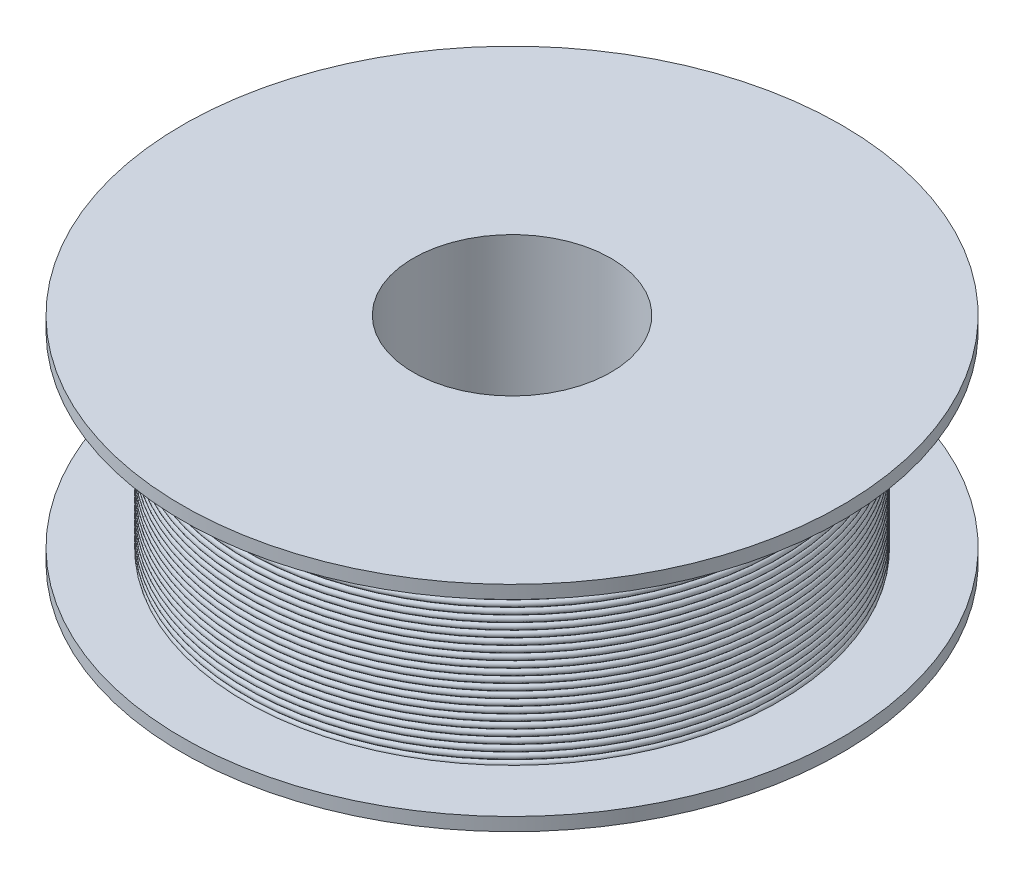
SolidWorks part; units mm, degrees
ref_plane "Front Plane" through (0, 0, 0) normal (0, 0, 1) x (1, 0, 0)
ref_plane "Top Plane" through (0, 0, 0) normal (0, 1, 0) x (1, 0, 0)
ref_plane "Right Plane" through (0, 0, 0) normal (1, 0, 0) x (0, 0, -1)
sketch "Sketch1" plane through (0, 0, 0) normal (0, 0, 1) x (1, 0, 0)
  line L0 (0, 0) -> (0, 65) construction
  line L1 (30, 65) -> (100, 65)
  line L2 (100, 65) -> (100, 61)
  line L3 (100, 61) -> (40, 61)
  line L4 (40, 61) -> (40, 4)
  line L5 (40, 4) -> (100, 4)
  line L6 (100, 4) -> (100, 0)
  line L7 (100, 0) -> (30, 0)
  line L8 (30, 65) -> (30, 0)
  line L9 (0, 65) -> (30, 65) construction
  line L10 (30, 0) -> (0, 0) construction
  dimension "D1" = 4
  dimension "D2" = 65
  dimension "D3" = 60
  dimension "D4" = 10
  dimension "D5" = 200
revolve "Revolve1" add sketch "Sketch1" angle 360 about L0
sketch "Sketch2" plane through (0, 0, 0) normal (0, 0, 1) x (1, 0, 0)
  line L0 (-100, 61) -> (100, 61) construction
  line L1 (-80, 61) -> (-80, 4)
  line L2 (100, 4) -> (-100, 4) construction
  line L3 (-80, 4) -> (-81, 4)
  line L4 (0, 0) -> (0, 66.8668) construction
  arc A0 (-80, 61) -> (-80, 59) centre (-80, 60) ccw
  arc A1 (-80, 59) -> (-80, 57) centre (-80, 58) ccw
  arc A2 (-80, 57) -> (-80, 55) centre (-80, 56) ccw
  arc A3 (-80, 55) -> (-80, 53) centre (-80, 54) ccw
  arc A4 (-80, 53) -> (-80, 51) centre (-80, 52) ccw
  arc A5 (-80, 51) -> (-80, 49) centre (-80, 50) ccw
  arc A6 (-80, 49) -> (-80, 47) centre (-80, 48) ccw
  arc A7 (-80, 47) -> (-80, 45) centre (-80, 46) ccw
  arc A8 (-80, 45) -> (-80, 43) centre (-80, 44) ccw
  arc A9 (-80, 43) -> (-80, 41) centre (-80, 42) ccw
  arc A10 (-80, 41) -> (-80, 39) centre (-80, 40) ccw
  arc A11 (-80, 39) -> (-80, 37) centre (-80, 38) ccw
  arc A12 (-80, 37) -> (-80, 35) centre (-80, 36) ccw
  arc A13 (-80, 35) -> (-80, 33) centre (-80, 34) ccw
  arc A14 (-80, 33) -> (-80, 31) centre (-80, 32) ccw
  arc A15 (-80, 31) -> (-80, 29) centre (-80, 30) ccw
  arc A16 (-80, 29) -> (-80, 27) centre (-80, 28) ccw
  arc A17 (-80, 27) -> (-80, 25) centre (-80, 26) ccw
  arc A18 (-80, 25) -> (-80, 23) centre (-80, 24) ccw
  arc A19 (-80, 23) -> (-80, 21) centre (-80, 22) ccw
  arc A20 (-80, 21) -> (-80, 19) centre (-80, 20) ccw
  arc A21 (-80, 19) -> (-80, 17) centre (-80, 18) ccw
  arc A22 (-80, 17) -> (-80, 15) centre (-80, 16) ccw
  arc A23 (-80, 15) -> (-80, 13) centre (-80, 14) ccw
  arc A24 (-80, 13) -> (-80, 11) centre (-80, 12) ccw
  arc A25 (-80, 11) -> (-80, 9) centre (-80, 10) ccw
  arc A26 (-80, 9) -> (-80, 7) centre (-80, 8) ccw
  arc A27 (-80, 7) -> (-80, 5) centre (-80, 6) ccw
  arc A28 (-80, 5) -> (-81, 4) centre (-80, 4) ccw
  dimension "D1" = 2
  dimension "D3" = 80
  dimension "D2" = 29
revolve "Revolve2" add sketch "Sketch2" angle 360 about L4
